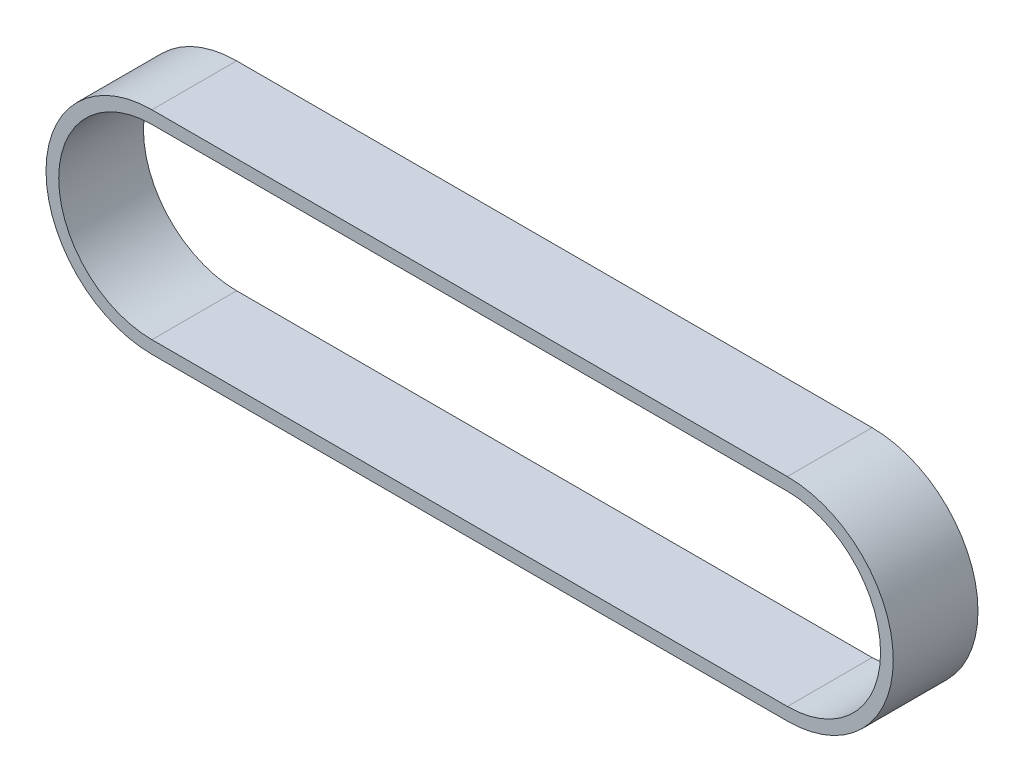
SolidWorks part; units mm, degrees
material "Rubber"
ref_plane "Front Plane" through (0, 0, 0) normal (0, 0, 1) x (1, 0, 0)
ref_plane "Top Plane" through (0, 0, 0) normal (0, 1, 0) x (1, 0, 0)
ref_plane "Right Plane" through (0, 0, 0) normal (1, 0, 0) x (0, 0, -1)
sketch "Sketch2" plane through (0, 0, 0) normal (0, 0, 1) x (1, 0, 0)
  line L0 (0, 0) -> (1, 0) construction
  line L1 (0, 0) -> (0, 1) construction
  line L2 (0.0062, -44) -> (-299.9938, -44.0423)
  line L3 (-300.0062, 43.9577) -> (-0.0062, 44)
  arc A0 (-0.0062, 44) -> (0.0062, -44) centre (0, 0) cw
  arc A1 (-299.9938, -44.0423) -> (-300.0062, 43.9577) centre (-300, -0.0423) cw
extrude "Extrude-Thin1" add sketch "Sketch2" along normal mid plane 40 thin thin type one direction wall 6
